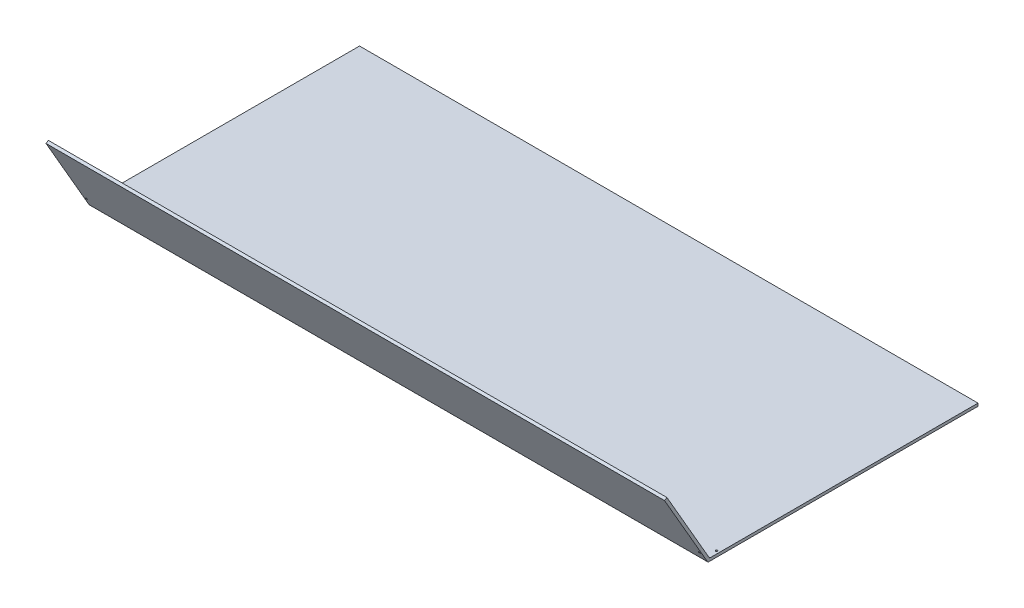
SolidWorks part; units mm, degrees
material "PPE"
ref_plane "Front Plane" through (0, 0, 0) normal (0, 0, 1) x (1, 0, 0)
ref_plane "Top Plane" through (0, 0, 0) normal (0, 1, 0) x (1, 0, 0)
ref_plane "Right Plane" through (0, 0, 0) normal (1, 0, 0) x (0, 0, -1)
sketch "Sketch1" plane through (0, 0, 0) normal (0, 1, 0) x (1, 0, 0)
  line L1 (-525.018, -228.6) -> (525.018, -228.6)
  line L2 (-525.018, -228.6) -> (-525.018, 228.6)
  line L3 (-525.018, 228.6) -> (525.018, 228.6)
  line L4 (525.018, -228.6) -> (525.018, 228.6)
  line L5 (-525.018, -228.6) -> (136.1971, 59.3021) construction
  line L6 (-525.018, 228.6) -> (525.018, -228.6) construction
  line L7 (-525.018, -228.6) -> (525.018, 228.6) construction
  point P0 (0, 0)
  dimension "D4" = 457.2
  dimension "D5" = 1050.036
extrude "Boss-Extrude1" add sketch "Sketch1" along normal blind 4.7625
sketch "Sketch2" plane through (-525.018, 0, 0) normal (-1, 0, 0) x (0, 0, 1)
  line L0 (228.6, 4.7625) -> (228.6, 0) construction
  line L1 (228.6, 4.7625) -> (228.6, 0)
  arc A0 (228.6, 0) -> (228.6, 4.7625) centre (228.6, 2.3813) ccw
extrude "Boss-Extrude2" add sketch "Sketch2" against normal up to surface (1050.036 mm away) up to face at (525.018, 2.3813, 0)
sketch "Sketch6"
  dimension "D1" = 7.9375
  dimension "D2" = 7.9375
  dimension "D3" = 4.7625
extrude "Cut-Extrude1" [suppressed] cut sketch "Sketch6" against normal up to next
sketch "Sketch9" plane through (0, 4.7625, 0) normal (0, 1, 0) x (1, 0, 0)
  line L0 (-520.2555, -210.3923) -> (520.2555, -210.3923) construction
  line L1 (525.018, -228.6) -> (525.018, 228.6) construction
  line L2 (-525.018, -228.6) -> (525.018, -228.6) construction
  circle A0 centre (520.2555, -210.3923) radius 1.5875
  circle A1 centre (-520.2555, -210.3923) radius 1.5875
  point P3 (0, -210.3923)
  dimension "D1" = 3.175
  dimension "D2" = 4.7625
  dimension "D3" = 18.2077
extrude "Cut-Extrude3" cut sketch "Sketch9" against normal through all
pattern_circular "CirPattern1" count 2 every 120 about axis through (0, 2.3812, 228.6) along (1, 0, 0) of "Boss-Extrude1", "Cut-Extrude3"
pattern_circular "CirPattern2" [suppressed] count 2 every 120
sketch "Sketch8" plane through (0, -97.2008, 168.3567) normal (0, 0.5, -0.866) x (-1, 0, 0)
  line L0 (525.018, 573.5622) -> (525.018, 117.737) construction
  line L1 (-525.018, 573.5622) -> (525.018, 573.5622)
  line L2 (-525.018, 573.5622) -> (-525.018, 262.4122)
  line L3 (-525.018, 262.4122) -> (525.018, 262.4122)
  line L4 (525.018, 573.5622) -> (525.018, 262.4122)
  dimension "D1" = 311.15
extrude "Cut-Extrude2" cut sketch "Sketch8" against normal up to next
fillet "Fillet1" radius 2.3813 1 edges at (0, 4.7625, 227.2252)
